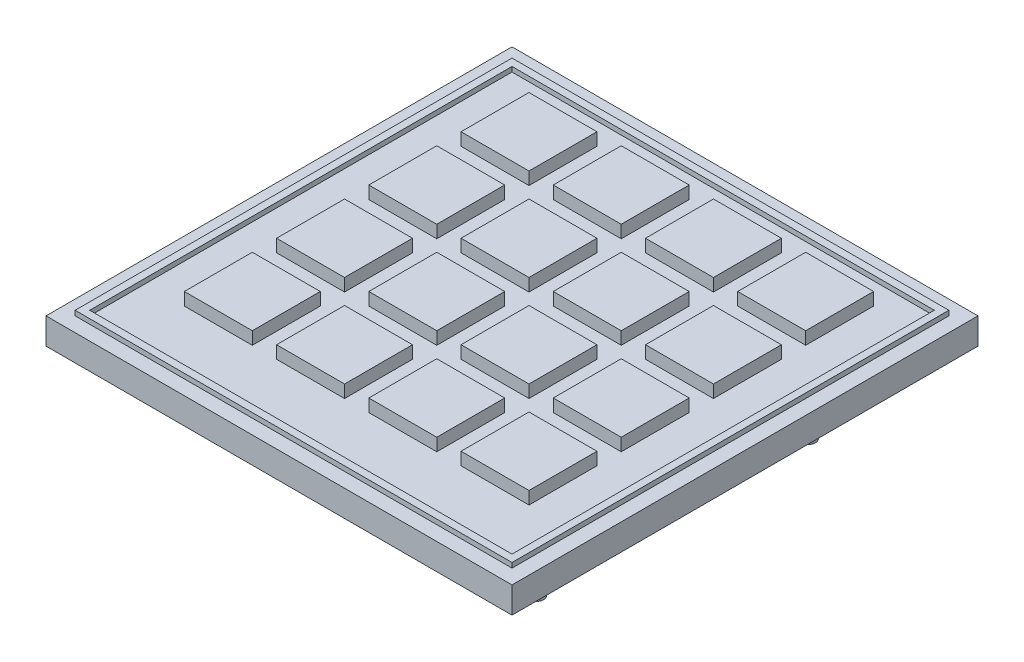
SolidWorks part; units mm, degrees
ref_plane "Спереди" through (0, 0, 0) normal (0, 0, 1) x (1, 0, 0)
ref_plane "Сверху" through (0, 0, 0) normal (0, 1, 0) x (1, 0, 0)
ref_plane "Справа" through (0, 0, 0) normal (1, 0, 0) x (0, 0, -1)
sketch "Эскиз1" plane through (0, 0, 0) normal (0, 1, 0) x (1, 0, 0)
  line L1 (-41.5267, 50.1116) -> (54.4733, 50.1116)
  line L2 (-41.5267, 50.1116) -> (-41.5267, -45.8884)
  line L3 (-41.5267, -45.8884) -> (54.4733, -45.8884)
  line L4 (54.4733, 50.1116) -> (54.4733, -45.8884)
  dimension "D1" = 96
  dimension "D2" = 96
extrude "Бобышка-Вытянуть1" add sketch "Эскиз1" along normal blind 5.4
sketch "Эскиз2" plane through (0, 5.4, 0) normal (0, 1, 0) x (1, 0, 0)
  line L0 (-29.0267, 53.6988) -> (-29.0267, -49.2784) construction
  line L1 (-49.3554, 41.1116) -> (69.9956, 41.1116) construction
  line L2 (54.4733, 50.1116) -> (-41.5267, 50.1116) construction
  line L3 (-41.5267, 50.1116) -> (-41.5267, -45.8884) construction
  line L4 (-10.0267, 41.1116) -> (3.9733, 41.1116)
  line L5 (-29.0267, 41.1116) -> (-15.0267, 41.1116)
  line L6 (-29.0267, 41.1116) -> (-29.0267, 27.1116)
  line L7 (-29.0267, 27.1116) -> (-15.0267, 27.1116)
  line L8 (-15.0267, 41.1116) -> (-15.0267, 27.1116)
  line L9 (-10.0267, 41.1116) -> (-10.0267, 27.1116)
  line L10 (-10.0267, 27.1116) -> (3.9733, 27.1116)
  line L11 (3.9733, 41.1116) -> (3.9733, 27.1116)
  line L12 (8.9733, 41.1116) -> (22.9733, 41.1116)
  line L13 (8.9733, 41.1116) -> (8.9733, 27.1116)
  line L14 (8.9733, 27.1116) -> (22.9733, 27.1116)
  line L15 (22.9733, 41.1116) -> (22.9733, 27.1116)
  line L16 (27.9733, 41.1116) -> (41.9733, 41.1116)
  line L17 (27.9733, 41.1116) -> (27.9733, 27.1116)
  line L18 (27.9733, 27.1116) -> (41.9733, 27.1116)
  line L19 (41.9733, 41.1116) -> (41.9733, 27.1116)
  line L20 (-10.0267, 22.1116) -> (3.9733, 22.1116)
  line L21 (-29.0267, 22.1116) -> (-15.0267, 22.1116)
  line L22 (-29.0267, 22.1116) -> (-29.0267, 8.1116)
  line L23 (-29.0267, 8.1116) -> (-15.0267, 8.1116)
  line L24 (-15.0267, 22.1116) -> (-15.0267, 8.1116)
  line L25 (-10.0267, 22.1116) -> (-10.0267, 8.1116)
  line L26 (-10.0267, 8.1116) -> (3.9733, 8.1116)
  line L27 (3.9733, 22.1116) -> (3.9733, 8.1116)
  line L28 (8.9733, 22.1116) -> (22.9733, 22.1116)
  line L29 (8.9733, 22.1116) -> (8.9733, 8.1116)
  line L30 (8.9733, 8.1116) -> (22.9733, 8.1116)
  line L31 (22.9733, 22.1116) -> (22.9733, 8.1116)
  line L32 (27.9733, 22.1116) -> (41.9733, 22.1116)
  line L33 (27.9733, 22.1116) -> (27.9733, 8.1116)
  line L34 (27.9733, 8.1116) -> (41.9733, 8.1116)
  line L35 (41.9733, 22.1116) -> (41.9733, 8.1116)
  line L36 (-10.0267, 3.1116) -> (3.9733, 3.1116)
  line L37 (-29.0267, 3.1116) -> (-15.0267, 3.1116)
  line L38 (-29.0267, 3.1116) -> (-29.0267, -10.8884)
  line L39 (-29.0267, -10.8884) -> (-15.0267, -10.8884)
  line L40 (-15.0267, 3.1116) -> (-15.0267, -10.8884)
  line L41 (-10.0267, 3.1116) -> (-10.0267, -10.8884)
  line L42 (-10.0267, -10.8884) -> (3.9733, -10.8884)
  line L43 (3.9733, 3.1116) -> (3.9733, -10.8884)
  line L44 (8.9733, 3.1116) -> (22.9733, 3.1116)
  line L45 (8.9733, 3.1116) -> (8.9733, -10.8884)
  line L46 (8.9733, -10.8884) -> (22.9733, -10.8884)
  line L47 (22.9733, 3.1116) -> (22.9733, -10.8884)
  line L48 (27.9733, 3.1116) -> (41.9733, 3.1116)
  line L49 (27.9733, 3.1116) -> (27.9733, -10.8884)
  line L50 (27.9733, -10.8884) -> (41.9733, -10.8884)
  line L51 (41.9733, 3.1116) -> (41.9733, -10.8884)
  line L52 (-10.0267, -15.8884) -> (3.9733, -15.8884)
  line L53 (-29.0267, -15.8884) -> (-15.0267, -15.8884)
  line L54 (-29.0267, -15.8884) -> (-29.0267, -29.8884)
  line L55 (-29.0267, -29.8884) -> (-15.0267, -29.8884)
  line L56 (-15.0267, -15.8884) -> (-15.0267, -29.8884)
  line L57 (-10.0267, -15.8884) -> (-10.0267, -29.8884)
  line L58 (-10.0267, -29.8884) -> (3.9733, -29.8884)
  line L59 (3.9733, -15.8884) -> (3.9733, -29.8884)
  line L60 (8.9733, -15.8884) -> (22.9733, -15.8884)
  line L61 (8.9733, -15.8884) -> (8.9733, -29.8884)
  line L62 (8.9733, -29.8884) -> (22.9733, -29.8884)
  line L63 (22.9733, -15.8884) -> (22.9733, -29.8884)
  line L64 (27.9733, -15.8884) -> (41.9733, -15.8884)
  line L65 (27.9733, -15.8884) -> (27.9733, -29.8884)
  line L66 (27.9733, -29.8884) -> (41.9733, -29.8884)
  line L67 (41.9733, -15.8884) -> (41.9733, -29.8884)
  dimension "D1" = 9
  dimension "D2" = 12.5
  dimension "D3" = 14
  dimension "D4" = 14
  dimension "D5" = 4
  dimension "D6" = 4
extrude "Бобышка-Вытянуть2" add sketch "Эскиз2" along normal blind 2.6
sketch "Эскиз4" plane through (0, 5.4, 0) normal (0, 1, 0) x (1, 0, 0)
  line L0 (-41.5267, 50.1116) -> (-41.5267, -45.8884) construction
  line L1 (-38.5267, 47.1116) -> (51.4733, 47.1116)
  line L2 (-38.5267, 47.1116) -> (-38.5267, -42.8884)
  line L3 (-38.5267, -42.8884) -> (51.4733, -42.8884)
  line L4 (51.4733, 47.1116) -> (51.4733, -42.8884)
  line L5 (54.4733, -45.8884) -> (54.4733, 50.1116) construction
  line L6 (54.4733, 50.1116) -> (-41.5267, 50.1116) construction
  line L7 (-41.5267, -45.8884) -> (54.4733, -45.8884) construction
  dimension "D1" = 3
  dimension "D2" = 3
  dimension "D3" = 3
  dimension "D4" = 3
extrude "Вытянуть-Тонкостенный1" add sketch "Эскиз4" along normal blind 1 thin contours L2 L3 L4 L1
sketch "Эскиз5" plane through (0, 0, 0) normal (0, -1, 0) x (1, 0, 0)
  line L0 (-57.2464, 25.8884) -> (49942.7536, 25.8884) construction
  line L1 (-52.5118, -30.1116) -> (49947.4882, -30.1116) construction
  line L2 (-41.5267, 45.8884) -> (54.4733, 45.8884) construction
  line L3 (54.4733, -50.1116) -> (-41.5267, -50.1116) construction
  line L4 (-26.5267, 49.4756) -> (-26.5267, -56.0661) construction
  line L5 (39.4733, 49.4756) -> (39.4733, -56.0661) construction
  line L6 (-41.5267, -50.1116) -> (-41.5267, 45.8884) construction
  line L7 (54.4733, 45.8884) -> (54.4733, -50.1116) construction
  circle A0 centre (39.4733, 25.8884) radius 1.5
  circle A1 centre (-26.5267, 25.8884) radius 1.5
  circle A2 centre (-26.5267, -30.1116) radius 1.5
  circle A3 centre (39.4733, -30.1116) radius 1.5
  dimension "D1" = 20
  dimension "D2" = 20
  dimension "D3" = 15
  dimension "D4" = 15
extrude "Бобышка-Вытянуть3" add sketch "Эскиз5" along normal blind 14
